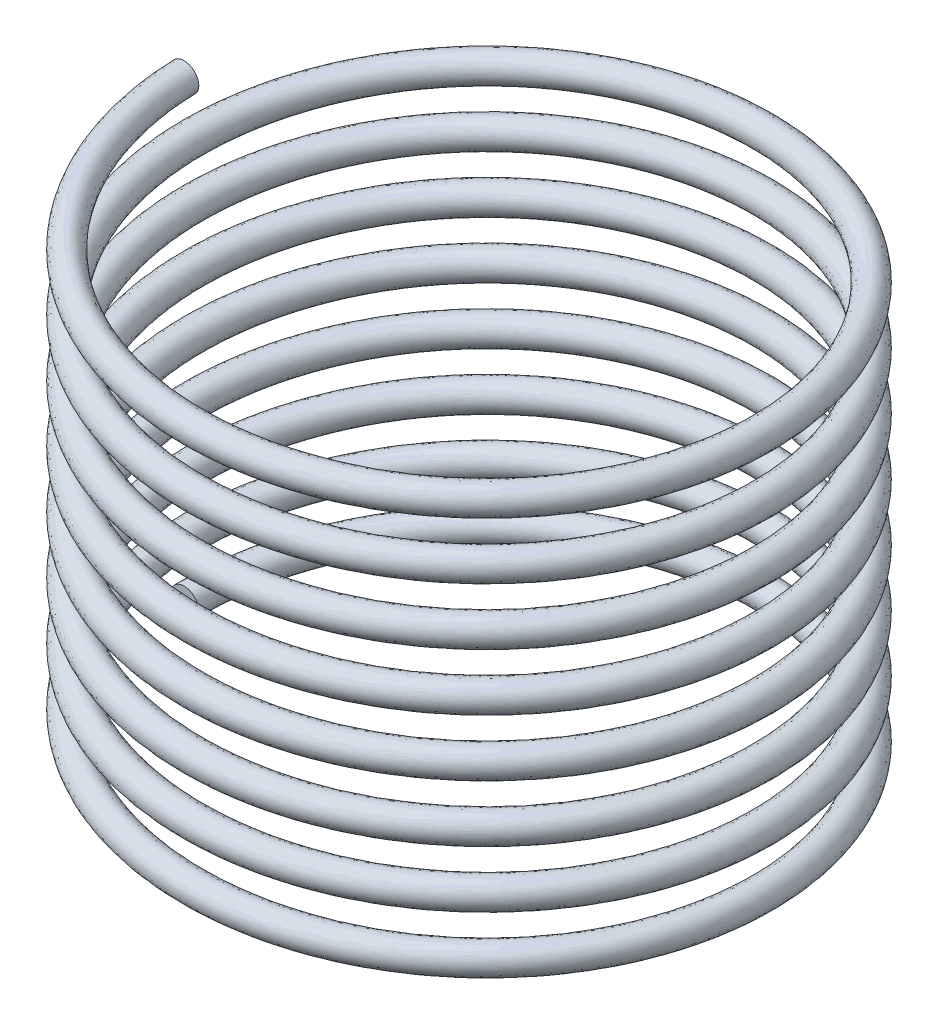
SolidWorks part; units mm, degrees
ref_plane "Front Plane" through (0, 0, 0) normal (0, 0, 1) x (1, 0, 0)
ref_plane "Top Plane" through (0, 0, 0) normal (0, 1, 0) x (1, 0, 0)
ref_plane "Right Plane" through (0, 0, 0) normal (1, 0, 0) x (0, 0, -1)
sketch "Sketch1" plane through (0, 0, 0) normal (0, 1, 0) x (1, 0, 0)
  circle A0 centre (0, 0) radius 50
  dimension "D1" = 100
curve "Helix/Spiral1" pitch 10 height 80 turns 8
sweep "Sweep1" add path "Helix/Spiral1" circular profile diameter 5 parameters "D3"=5
